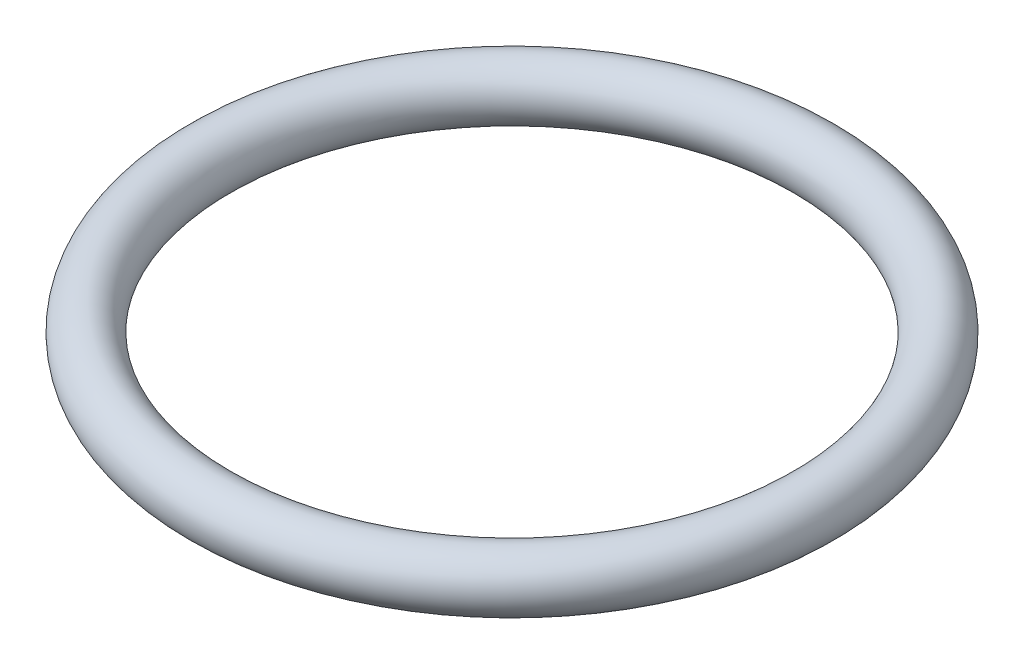
SolidWorks part; units mm, degrees
ref_plane "Face" through (0, 0, 0) normal (0, 0, 1) x (1, 0, 0)
ref_plane "Dessus" through (0, 0, 0) normal (0, 1, 0) x (1, 0, 0)
ref_plane "Droite" through (0, 0, 0) normal (1, 0, 0) x (0, 0, -1)
sketch "Esquisse1" plane through (0, 0, 0) normal (0, 0, 1) x (1, 0, 0)
  line L0 (0, 13.1713) -> (0, -7.2863) construction
  circle A0 centre (6.4, 0) radius 0.6
  dimension "D1" = 1.2
  dimension "D2" = 6.4
revolve "Base-Révolution" add sketch "Esquisse1" angle 360 about L0
